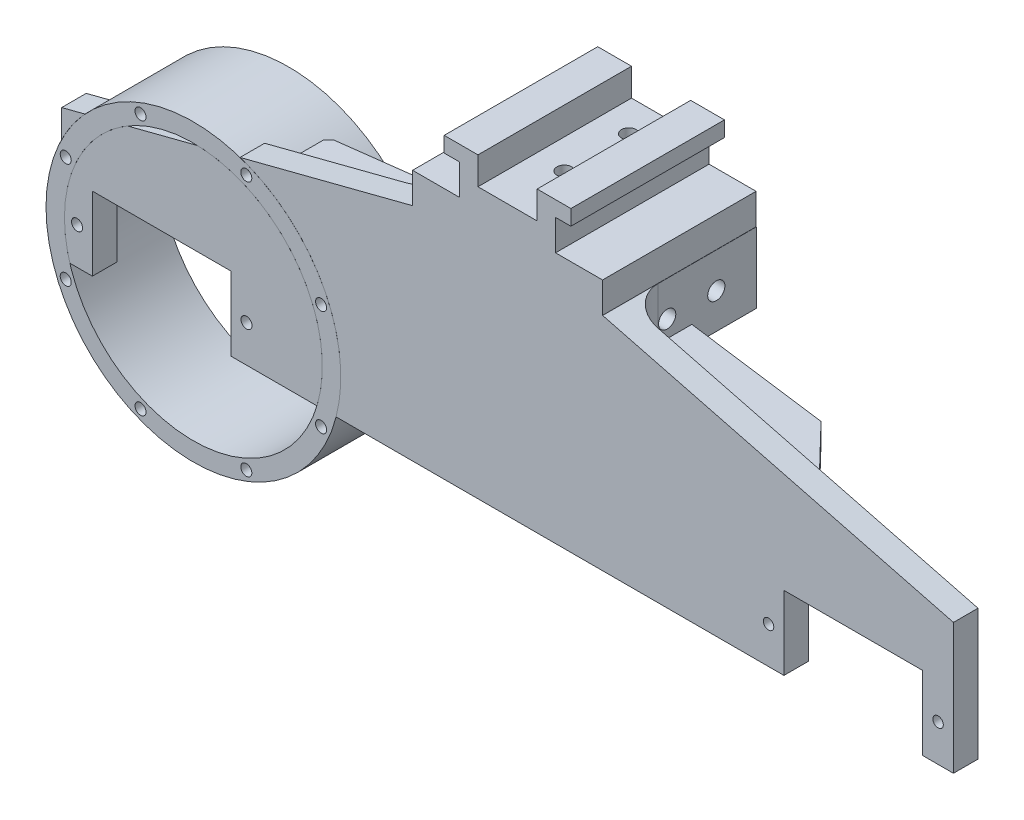
SolidWorks part; units mm, degrees
ref_plane "Plan de face" through (0, 0, 0) normal (0, 0, 1) x (1, 0, 0)
ref_plane "Plan de dessus" through (0, 0, 0) normal (0, 1, 0) x (1, 0, 0)
ref_plane "Plan de droite" through (0, 0, 0) normal (1, 0, 0) x (0, 0, -1)
sketch "Esquisse1" plane through (0, 0, 0) normal (0, 0, 1) x (1, 0, 0)
  line L0 (0, -6) -> (0, 18) construction
  line L1 (15.5, 18) -> (-15.5, 18)
  line L2 (0, -6) -> (0, -18) construction
  line L3 (0, -18) -> (-72.6, -18) construction
  line L4 (-72.6, 12.5574) -> (-72.6, -6) construction
  line L7 (0, -6) -> (-72.6, -6) construction
  line L8 (-40, 12) -> (-40, -18) construction
  line L9 (-10.5, 18) -> (-10.5, -6) construction
  line L10 (-45, -6) -> (-45, -18) construction
  line L11 (-67.6, -6) -> (-67.6, -18) construction
  line L12 (-72.6, -6) -> (-72.6, -18) construction
  line L13 (-45, -12) -> (-40, -12) construction
  line L14 (-45, -12) -> (-72.6, -12) construction
  line L15 (-15.5, 18) -> (-15.5, -6) construction
  line L16 (45, -18) -> (45, -6)
  line L17 (45, -18) -> (-45, -18)
  line L18 (-45, -18) -> (-45, -6)
  line L19 (-45, -6) -> (-67.6, -6)
  line L20 (-67.6, -6) -> (-67.6, -18)
  line L21 (-67.6, -18) -> (-72.6, -18)
  line L22 (-72.6, -18) -> (-72.6, 3.2787)
  line L23 (-72.6, 3.2787) -> (-15.5, 18)
  line L24 (45, -6) -> (67.6, -6)
  line L25 (67.6, -6) -> (67.6, -18)
  line L26 (67.6, -18) -> (72.6, -18)
  line L27 (72.6, -18) -> (72.6, 3.2787)
  line L28 (72.6, 3.2787) -> (15.5, 18)
  line L29 (-72.6, -12) -> (-67.6, -12) construction
  circle A0 centre (-42.5, -12) radius 0.85
  circle A1 centre (-70.1, -12) radius 0.85
  circle A2 centre (42.5, -12) radius 0.85
  circle A3 centre (70.1, -12) radius 0.85
  point P0 (0, 0)
  dimension "D8" = 12
  dimension "D1" = 24
  dimension "D2" = 40
  dimension "D3" = 10.5
  dimension "D4" = 5
  dimension "D5" = 22.6
  dimension "D6" = 5
  dimension "D7" = 5
extrude "Boss.-Extru.1" add sketch "Esquisse1" along normal blind 4
sketch "Esquisse2" plane through (0, 0, 0) normal (0, 0, -1) x (-1, 0, 0)
  line L0 (0, 18) -> (0, -18) construction
  line L1 (-15.5, 18) -> (15.5, 18) construction
  line L2 (45, -18) -> (-45, -18) construction
  line L3 (10.5, 18) -> (10.5, 6.5) construction
  line L4 (10.5, 6.5) -> (0, 6.5) construction
  line L5 (-15.5, 6.5) -> (-15.5, 18)
  line L6 (10.5, 6.5) -> (15.5, 6.5)
  line L7 (10.5, 6.5) -> (10.5, 18)
  line L8 (10.5, 18) -> (15.5, 18)
  line L9 (15.5, 6.5) -> (15.5, 18)
  line L10 (-10.5, 6.5) -> (-15.5, 6.5)
  line L11 (-10.5, 6.5) -> (-10.5, 18)
  line L12 (-10.5, 18) -> (-15.5, 18)
  dimension "D1" = 10.5
  dimension "D2" = 11.5
  dimension "D3" = 5
extrude "Boss.-Extru.2" add sketch "Esquisse2" along normal blind 21
sketch "Esquisse3" plane through (-15.5, 0, 0) normal (-1, 0, 0) x (0, 0, 1)
  line L0 (0, 12.25) -> (-21, 12.25) construction
  line L1 (0, 6.5) -> (0, 18) construction
  line L2 (-21, 6.5) -> (-21, 18) construction
  circle A0 centre (-6.49, 12.25) radius 1.4
  circle A1 centre (-14.49, 12.25) radius 1.4
  dimension "D1" = 6.49
  dimension "D2" = 8
extrude "Enlèv. mat.-Extru.1" cut sketch "Esquisse3" against normal through all
fillet "Congé1" radius 5 2 edges at (15.5, 12.25, 0) (-15.5, 12.25, 0)
sketch "Esquisse4" plane through (0, 6.5, 0) normal (0, -1, 0) x (1, 0, 0)
  line L0 (-10.5, -10.5) -> (-15.5, -10.5) construction
  line L1 (-10.5, -21) -> (-10.5, 0) construction
  line L2 (-15.5, -21) -> (-15.5, -5) construction
  line L3 (-15.5, -10.5) -> (-39.7032, -7.3409)
  line L4 (-39.7032, -7.3409) -> (-46.7873, 0)
  line L5 (-46.7873, 0) -> (-10.5, 0)
  line L6 (-45, 0) -> (45, 0) construction
  line L7 (-10.5, 0) -> (-20.5, 0) construction
  line L8 (-10.5, 0) -> (-10.5, -10.5)
  line L9 (0, 0) -> (0, -22.1849) construction
  line L10 (-15.5, -10.5) -> (-10.5, -10.5)
  line L11 (15.5, -10.5) -> (10.5, -10.5)
  line L12 (15.5, -10.5) -> (39.7032, -7.3409)
  line L13 (39.7032, -7.3409) -> (46.7873, 0)
  line L14 (46.7873, 0) -> (10.5, 0)
  line L15 (10.5, 0) -> (10.5, -10.5)
  line L16 (-67.6, 0) -> (-45, 0) construction
extrude "Boss.-Extru.3" add sketch "Esquisse4" against normal blind 3
sketch "Esquisse5" plane through (0, 0, 4) normal (0, 0, 1) x (1, 0, 0)
  line L0 (-15.4662, 23) -> (-15.4662, 18)
  line L1 (-15.4662, 18) -> (15.4662, 18)
  line L2 (15.4662, 23) -> (15.4662, 18)
  line L3 (7.8162, 23) -> (15.4662, 23)
  line L4 (7.8162, 28) -> (7.8162, 23)
  line L5 (10.3162, 28) -> (7.8162, 28)
  line L6 (10.3162, 30.5) -> (10.3162, 28)
  line L7 (4.8162, 26) -> (4.8162, 30.5)
  line L8 (4.8162, 30.5) -> (10.3162, 30.5)
  line L9 (-4.8162, 26) -> (4.8162, 26)
  line L10 (-4.8162, 26) -> (-4.8162, 30.5)
  line L11 (-4.8162, 30.5) -> (-10.3162, 30.5)
  line L12 (-10.3162, 30.5) -> (-10.3162, 28)
  line L13 (-10.3162, 28) -> (-7.8162, 28)
  line L14 (-7.8162, 28) -> (-7.8162, 23)
  line L15 (-7.8162, 23) -> (-15.4662, 23)
  line L16 (0, 18) -> (0, 37.9666) construction
  line L17 (0, 18) -> (0, 10.2712) construction
  line L18 (15.5, 18) -> (-15.5, 18) construction
  point P9 (0, 26)
  dimension "D1" = 5.5
  dimension "D2" = 2.5
  dimension "D3" = 4.5
  dimension "D4" = 5
  dimension "D5" = 7.65
  dimension "D6" = 5
  dimension "D7" = 15.4662
  dimension "D8" = 4.8162
  dimension "D9" = 0
  dimension "D10" = 0
extrude "Boss.-Extru.4" add sketch "Esquisse5" against normal through all
sketch "Esquisse6" plane through (0, 18, 0) normal (0, -1, 0) x (1, 0, 0)
  line L0 (-10.5, -10.5) -> (10.5, -10.5) construction
  line L2 (-10.5, -21) -> (-10.5, 0) construction
  line L3 (10.5, -21) -> (10.5, 0) construction
  line L4 (0, 0) -> (0, -10.5) construction
  line L5 (0, -21) -> (0, -10.5) construction
  line L6 (-15.4662, -21) -> (15.4662, -21) construction
  circle A0 centre (0, -5.25) radius 1.2
  circle A1 centre (0, -15.75) radius 1.2
extrude "Enlèv. mat.-Extru.2" cut sketch "Esquisse6" against normal through all
sketch "Esquisse9" plane through (0, 0, 0) normal (0, 0, -1) x (-1, 0, 0)
  line L0 (45, -12) -> (67.6, -12) construction
  line L1 (45, -6) -> (45, -18) construction
  line L2 (67.6, -18) -> (67.6, -6) construction
  line L3 (56.3, -12) -> (56.3, -7.7916) construction
  line L4 (51.15, -12) -> (51.15, -7.7916) construction
  circle A0 centre (51.15, -12) radius 21
  circle A1 centre (51.15, -12) radius 24
  circle A2 centre (51.15, -12) radius 22.5 construction
  point P30 (56.3, -12)
  point P33 (51.15, -12)
  dimension "D3" = 42
  dimension "D4" = 48
  dimension "D5" = 45
  dimension "D2" = 5.15
extrude "Boss.-Extru.6" add sketch "Esquisse9" along normal blind 4.5 and the other way through all
sketch "Esquisse10" plane through (0, 0, -4.5) normal (0, 0, -1) x (-1, 0, 0)
  line L0 (75.15, -12) -> (27.15, -12) construction
  line L1 (38.616, -9.75) -> (76.9338, -9.75) construction
  line L2 (38.616, -14.25) -> (76.9338, -14.25) construction
  line L3 (27.2557, -9.75) -> (30.2709, -9.75)
  line L4 (27.2557, -14.25) -> (30.2709, -14.25)
  line L5 (72.0291, -9.75) -> (75.0443, -9.75)
  line L6 (72.0291, -14.25) -> (75.0443, -14.25)
  circle A0 centre (51.15, -12) radius 24 construction
  arc A1 (30.2709, -14.25) -> (72.0291, -14.25) centre (51.15, -12) ccw
  arc A2 (27.2557, -14.25) -> (75.0443, -14.25) centre (51.15, -12) ccw
  arc A3 (72.0291, -9.75) -> (30.2709, -9.75) centre (51.15, -12) ccw
  arc A4 (75.0443, -9.75) -> (27.2557, -9.75) centre (51.15, -12) ccw
  circle A5 centre (51.15, -12) radius 21 construction
  dimension "D1" = 2.25
extrude "Boss.-Extru.7" add sketch "Esquisse10" along normal blind 7
sketch "Esquisse11" plane through (0, 0, 4) normal (0, 0, 1) x (1, 0, 0)
  line L0 (-67.6, -12) -> (-45, -12) construction
  line L1 (-67.6, -18) -> (-67.6, -6) construction
  line L2 (-45, -6) -> (-45, -18) construction
  line L3 (-67.6, -12) -> (-77.482, -12) construction
  line L4 (-45, -12) -> (-35.242, -12) construction
  line L5 (-56.3, -12) -> (-56.3, -8.4155) construction
  circle A0 centre (-70.1, -12) radius 0.9
  circle A1 centre (-42.5, -12) radius 0.9
  dimension "D1" = 13.8
  dimension "D2" = 13.8
extrude "Enlèv. mat.-Extru.3" cut sketch "Esquisse11" against normal through all and the other way through all
sketch "Esquisse12" plane through (0, 0, 4) normal (0, 0, 1) x (1, 0, 0)
  line L0 (-72.15, -12) -> (-30.15, -12) construction
  line L1 (-51.15, -12) -> (-71.9373, -3.3896) construction
  circle A0 centre (-51.15, -12) radius 21 construction
  arc A1 (-31.0254, -18) -> (-50.4534, 8.9884) centre (-51.15, -12) ccw construction
  circle A2 centre (-51.15, -12) radius 22.5 construction
  circle A3 centre (-71.9373, -3.3896) radius 0.9
  circle A4 centre (-59.7604, 8.7873) radius 0.9
  circle A5 centre (-42.5396, 8.7873) radius 0.9
  circle A6 centre (-30.3627, -3.3896) radius 0.9
  circle A7 centre (-30.3627, -20.6104) radius 0.9
  circle A8 centre (-42.5396, -32.7873) radius 0.9
  circle A9 centre (-59.7604, -32.7873) radius 0.9
  circle A10 centre (-71.9373, -20.6104) radius 0.9
  point P31 (-51.15, -12)
  dimension "D3" = 45
  dimension "D2" = 22.5
  dimension "D1" = 8
extrude "Enlèv. mat.-Extru.4" cut sketch "Esquisse12" against normal through all and the other way through all
